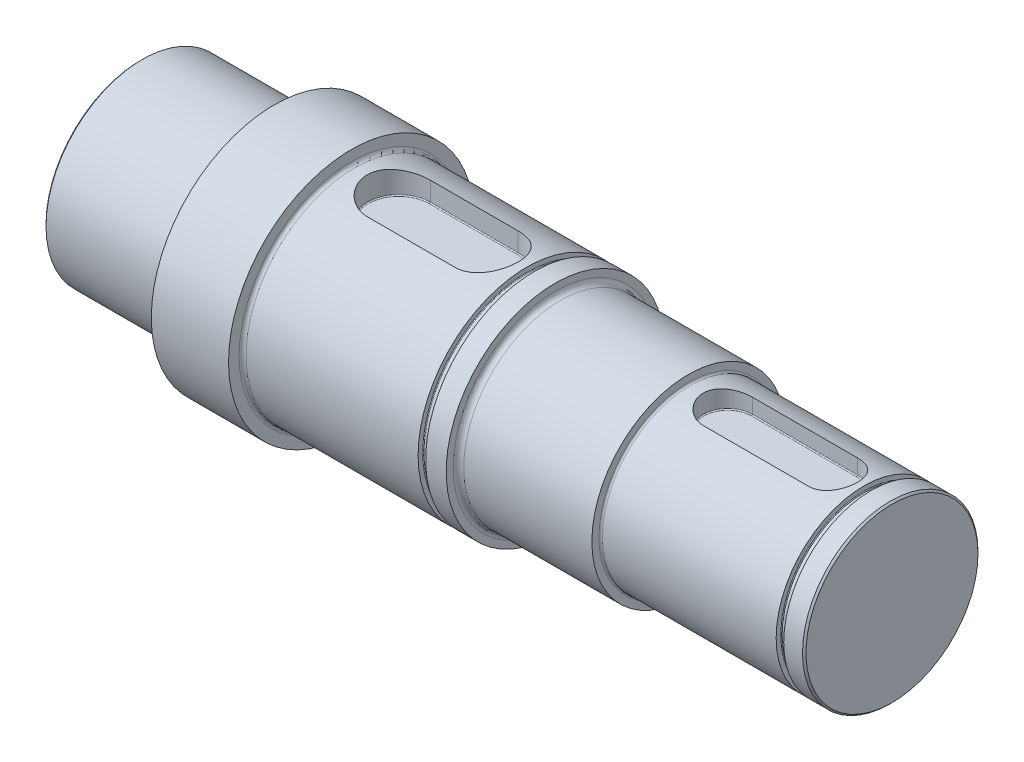
SolidWorks part; units mm, degrees
ref_plane "Front Plane" through (0, 0, 0) normal (0, 0, 1) x (1, 0, 0)
ref_plane "Top Plane" through (0, 0, 0) normal (0, 1, 0) x (1, 0, 0)
ref_plane "Right Plane" through (0, 0, 0) normal (1, 0, 0) x (0, 0, -1)
sketch "Sketch1" plane through (0, 0, 0) normal (1, 0, 0) x (0, 0, -1)
  circle A0 centre (0, 0) radius 35
  dimension "D1" = 70
extrude "Boss-Extrude1" add sketch "Sketch1" along normal mid plane 200
sketch "Sketch2" plane through (-100, 0, 0) normal (-1, 0, 0) x (0, 0, 1)
  circle A0 centre (0, 0) radius 27.5
  circle A1 centre (0, 0) radius 35 construction
  circle A2 centre (0, 0) radius 35
  dimension "D1" = 55
extrude "Cut-Extrude1" cut sketch "Sketch2" against normal blind 32
sketch "Sketch3" plane through (100, 0, 0) normal (1, 0, 0) x (0, 0, -1)
  circle A0 centre (0, 0) radius 25
  circle A1 centre (0, 0) radius 35 construction
  circle A2 centre (0, 0) radius 35
  dimension "D1" = 50
extrude "Cut-Extrude2" cut sketch "Sketch3" against normal blind 58
sketch "Sketch4" plane through (42, 0, 0) normal (1, 0, 0) x (0, 0, -1)
  circle A0 centre (0, 0) radius 27.5
  circle A1 centre (0, 0) radius 35 construction
  circle A2 centre (0, 0) radius 35
  dimension "D1" = 55
extrude "Cut-Extrude3" cut sketch "Sketch4" against normal blind 30
sketch "Sketch5" plane through (12, 0, 0) normal (1, 0, 0) x (0, 0, -1)
  circle A0 centre (0, 0) radius 31
  circle A1 centre (0, 0) radius 35 construction
  circle A2 centre (0, 0) radius 35
  dimension "D1" = 62
extrude "Cut-Extrude4" cut sketch "Sketch5" against normal blind 58
fillet "Fillet1" radius 1.5 2 edges at (12, 0, -27.5) (-68, 0, 27.5)
fillet "Fillet4" radius 1 1 edges at (-46, 0, -31)
sketch "Sketch9" plane through (0, 0, 0) normal (0, 0, 1) x (1, 0, 0)
  line L0 (-46, -35) -> (-46, 35) construction
  line L1 (4, 33.0725) -> (6.15, 33.0725)
  line L2 (4, 33.0725) -> (4, 29.5)
  line L3 (4, 29.5) -> (6.15, 29.5)
  line L4 (6.15, 33.0725) -> (6.15, 29.5)
  line L5 (12, 31) -> (-45, 31) construction
  line L6 (0, 0) -> (-8.9319, 0) construction
  dimension "D1" = 50
  dimension "D2" = 2.15
  dimension "D3" = 1.5
revolve "Cut-Revolve4" cut sketch "Sketch9" angle 360 about L6
fillet "Fillet8" radius 0.2 2 edges at (4, 0, -29.5) (6.15, 0, -29.5)
sketch "Sketch10" plane through (0, 0, 0) normal (0, 1, 0) x (1, 0, 0)
  line L0 (-46, -35) -> (-46, 35) construction
  line L1 (-7.5, -9) -> (-32.5, -9)
  line L3 (-7.5, 9) -> (-32.5, 9)
  line L5 (-7.5, -9) -> (-32.5, 9) construction
  line L6 (-7.5, 9) -> (-32.5, -9) construction
  arc A0 (-32.5, 9) -> (-32.5, -9) centre (-32.5, 0) ccw
  arc A1 (-7.5, 9) -> (-7.5, -9) centre (-7.5, 0) cw
  point P0 (-20, 0)
  dimension "D1" = 25
  dimension "D2" = 18
  dimension "D3" = 13.5
extrude "Cut-Extrude5" cut sketch "Sketch10" along normal up to surface (5.6648 mm away) from offset 24
sketch "Sketch12" plane through (-100, 0, 0) normal (-1, 0, 0) x (0, 0, 1)
  circle A1 centre (0, 0) radius 27.5
  circle A2 centre (0, 0) radius 27.5
  dimension "D1" = 0
extrude "Boss-Extrude2" add sketch "Sketch12" along normal blind 6
chamfer "Chamfer1" distance 0.5 angle 45 1 edges at (-106, 0, 27.5)
sketch "Sketch13" plane through (100, 0, 0) normal (1, 0, 0) x (0, 0, -1)
  circle A1 centre (0, 0) radius 25
  circle A2 centre (0, 0) radius 25
  dimension "D1" = 0
extrude "Boss-Extrude3" add sketch "Sketch13" along normal blind 8
sketch "Sketch15" plane through (42, 0, 0) normal (1, 0, 0) x (0, 0, -1)
  circle A1 centre (0, 0) radius 27.5
  circle A2 centre (0, 0) radius 27.5
  dimension "D1" = 0
extrude "Boss-Extrude4" add sketch "Sketch15" along normal blind 8
sketch "Sketch17" plane through (0, 0, 0) normal (0, 0, 1) x (1, 0, 0)
  line L0 (50, -27.5) -> (50, 27.5) construction
  line L1 (100, 26.9336) -> (102.15, 26.9336)
  line L2 (100, 26.9336) -> (100, 23.5)
  line L3 (100, 23.5) -> (102.15, 23.5)
  line L4 (102.15, 26.9336) -> (102.15, 23.5)
  line L5 (108, 25) -> (50, 25) construction
  line L6 (80.6979, 0) -> (92.9992, 0) construction
  dimension "D1" = 50
  dimension "D2" = 2.15
  dimension "D3" = 1.5
revolve "Cut-Revolve5" cut sketch "Sketch17" angle 360 about L6
fillet "Fillet9" radius 0.2 2 edges at (100, 0, 23.5) (102.15, 0, 23.5)
chamfer "Chamfer2" distance 0.5 angle 45 1 edges at (108, 0, -25)
sketch "Sketch18" plane through (0, 0, 0) normal (0, 1, 0) x (1, 0, 0)
  line L0 (100.2, 23.5) -> (100.2, -23.5) construction
  line L1 (61.2, -7) -> (91.2, -7)
  line L3 (61.2, 7) -> (91.2, 7)
  line L5 (61.2, -7) -> (91.2, 7) construction
  line L6 (61.2, 7) -> (91.2, -7) construction
  arc A0 (91.2, 7) -> (91.2, -7) centre (91.2, 0) cw
  arc A1 (61.2, 7) -> (61.2, -7) centre (61.2, 0) ccw
  point P0 (76.2, 0)
  dimension "D1" = 30
  dimension "D2" = 14
  dimension "D3" = 24
extrude "Cut-Extrude6" cut sketch "Sketch18" along normal up to surface (4.5 mm away) from offset 19.5
fillet "Fillet10" radius 0.3 8 edges at (-20, 24, -9) (1.5, 24, 0) (-20, 24, 9) (-41.5, 24, 0) (76.2, 19.5, 7) (54.2, 19.5, 0) (76.2, 19.5, -7) (98.2, 19.5, 0)
fillet "Fillet11" radius 0.5 1 edges at (50, 0, -25)
